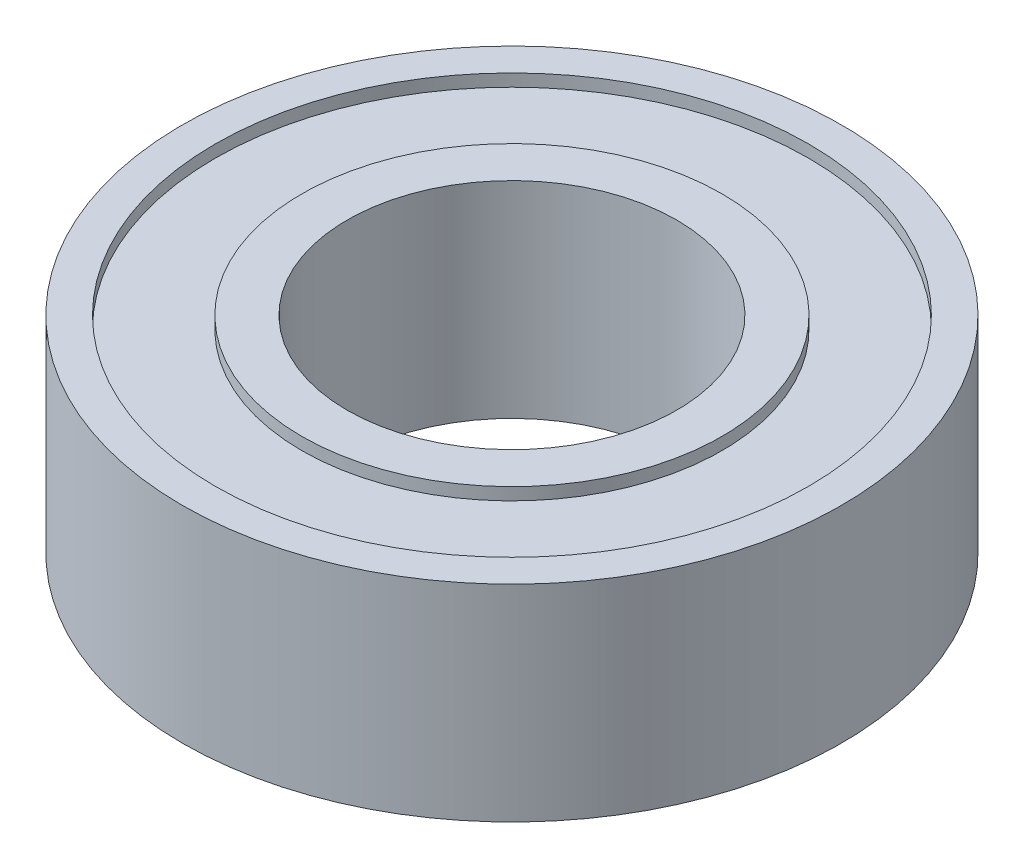
SolidWorks part; units mm, degrees
ref_plane "Front Plane" through (0, 0, 0) normal (0, 0, 1) x (1, 0, 0)
ref_plane "Top Plane" through (0, 0, 0) normal (0, 1, 0) x (1, 0, 0)
ref_plane "Right Plane" through (0, 0, 0) normal (1, 0, 0) x (0, 0, -1)
sketch "Sketch1" plane through (0, 0, 0) normal (1, 0, 0) x (0, 0, -1)
  line L0 (0, 4.825) -> (0, -4.825) construction
  line L1 (7.2, 2.5) -> (8, 2.5)
  line L2 (4, 2.5) -> (5.1, 2.5)
  line L3 (4, 2.5) -> (4, -2.5)
  line L4 (4, -2.5) -> (5.1, -2.5)
  line L5 (8, 2.5) -> (8, -2.5)
  line L6 (4, 2.5) -> (8, -2.5) construction
  line L7 (4, -2.5) -> (8, 2.5) construction
  line L9 (5.1, 2.5) -> (5.1, 2.2)
  line L10 (5.1, 2.2) -> (7.2, 2.2)
  line L11 (7.2, 2.5) -> (7.2, 2.2)
  line L13 (5.1, -2.5) -> (5.1, -2.2)
  line L14 (5.1, -2.2) -> (7.2, -2.2)
  line L15 (7.2, -2.5) -> (7.2, -2.2)
  line L16 (7.2, -2.5) -> (8, -2.5)
  point P0 (6, 0)
  point P4 (0, 0)
  dimension "D1" = 1.1
  dimension "D2" = 0.8
  dimension "D3" = 2.1
  dimension "D4" = 1.1
  dimension "D5" = 2.1
  dimension "D6" = 0.3
  dimension "D7" = 0.3
  dimension "D8" = 5
  dimension "D9" = 4
revolve "Revolve1" add sketch "Sketch1" angle 360 about L0
